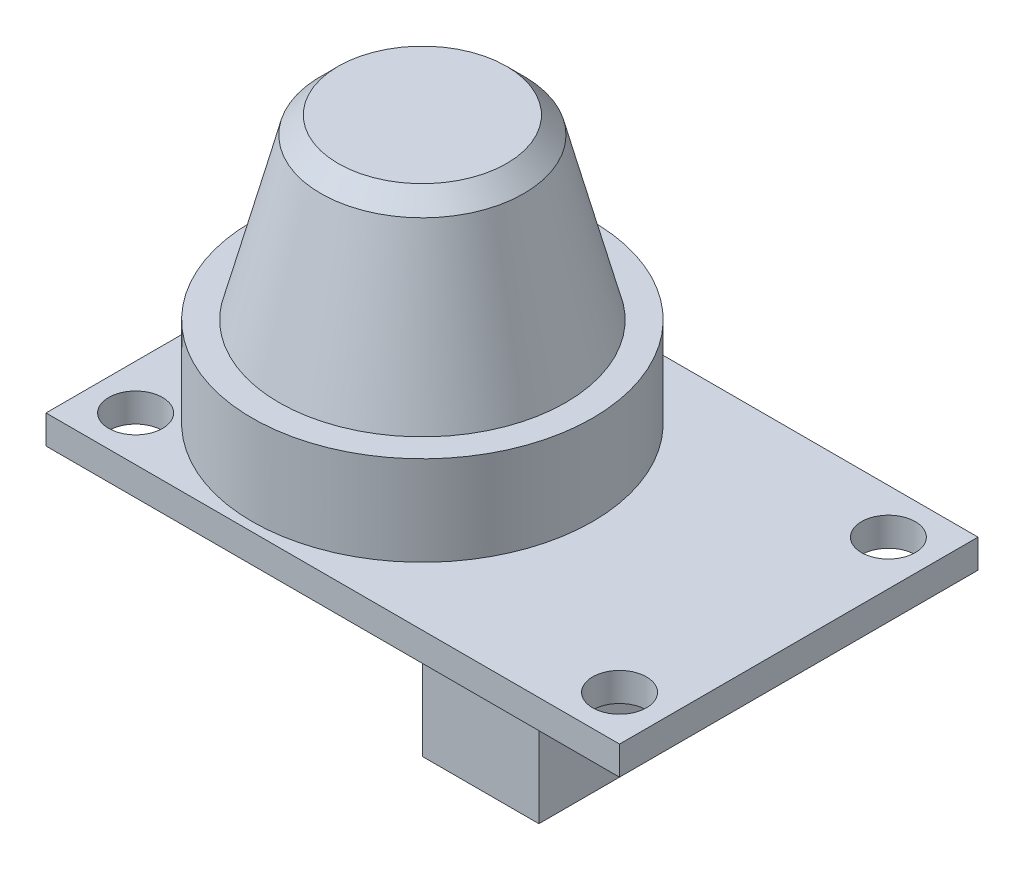
SolidWorks part; units mm, degrees
ref_plane "前视基准面" through (0, 0, 0) normal (0, 0, 1) x (1, 0, 0)
ref_plane "上视基准面" through (0, 0, 0) normal (0, 1, 0) x (1, 0, 0)
ref_plane "右视基准面" through (0, 0, 0) normal (1, 0, 0) x (0, 0, -1)
other "Configuration Table"
sketch "草图1" plane through (0, 0, 0) normal (0, 1, 0) x (1, 0, 0)
  line L1 (-16, 10) -> (16, 10)
  line L2 (-16, 10) -> (-16, -10)
  line L3 (-16, -10) -> (16, -10)
  line L4 (16, 10) -> (16, -10)
  line L5 (-16, 10) -> (16, -10) construction
  line L6 (-16, -10) -> (16, 10) construction
  circle A0 centre (-13.5, 7.5) radius 1.5
  circle A1 centre (13.5, 7.5) radius 1.5
  circle A2 centre (-13.5, -7.5) radius 1.5
  circle A3 centre (13.5, -7.5) radius 1.5
  point P0 (0, 0)
  dimension "D3" = 3
  dimension "D4" = 3
  dimension "D5" = 3
  dimension "D6" = 3
  dimension "D1" = 20
  dimension "D2" = 32
  dimension "D7" = 27
  dimension "D8" = 15
  dimension "D9" = 27
  dimension "D10" = 15
  dimension "D11" = 2.5
  dimension "D12" = 2.5
extrude "凸台-拉伸1" add sketch "草图1" along normal blind 1.6
sketch "草图2" plane through (0, 0, 0) normal (0, 1, 0) x (1, 0, 0)
  line L0 (-16, -10) -> (16, -10) construction
  line L1 (4.5, -9.5) -> (11, -9.5)
  line L2 (4.5, -9.5) -> (4.5, -3)
  line L3 (4.5, -3) -> (11, -3)
  line L4 (11, -9.5) -> (11, -3)
  line L5 (16, -10) -> (16, 10) construction
  dimension "D1" = 6.5
  dimension "D2" = 6.5
  dimension "D3" = 0.5
  dimension "D4" = 5
extrude "凸台-拉伸2" add sketch "草图2" against normal blind 5 from surface at 0 starting at face at (0, 0, 0)
sketch "草图3" plane through (0, 0, 0) normal (0, 1, 0) x (1, 0, 0)
  line L0 (-16, 10) -> (-16, -10) construction
  circle A0 centre (-5, 0) radius 9.5
  dimension "D1" = 19
  dimension "D2" = 11
extrude "凸台-拉伸3" add sketch "草图3" along normal blind 16.5
sketch "草图4" plane through (0, 0, 0) normal (0, 0, 1) x (1, 0, 0)
  line L0 (4.5, 16.5) -> (-14.5, 16.5) construction
  line L1 (4.5, 16.5) -> (-14.5, 16.5) construction
  line L2 (-5, -983.5) -> (-5, 49016.5) construction
  line L3 (0.6667, 15.5333) -> (3, 6.6)
  line L4 (3, 6.6) -> (4.5, 6.6)
  line L5 (4.5, 6.6) -> (4.5, 16.5)
  line L6 (4.5, 16.5) -> (0.5, 16.5)
  line L7 (0.6667, 15.5333) -> (-0.3, 16.5)
  line L8 (-0.3, 16.5) -> (0.5, 16.5)
  line L9 (-0.3, 16.5) -> (0.5, 16.5)
  point P2 (-5, 16.5)
  dimension "D1" = 9.9
  dimension "D2" = 4
  dimension "D3" = 1.5
  dimension "D4" = 0.8
  dimension "D5" = 45
  dimension "D6" = 8.9333
revolve "切除-旋转2" cut sketch "草图4" angle 360 about L2
